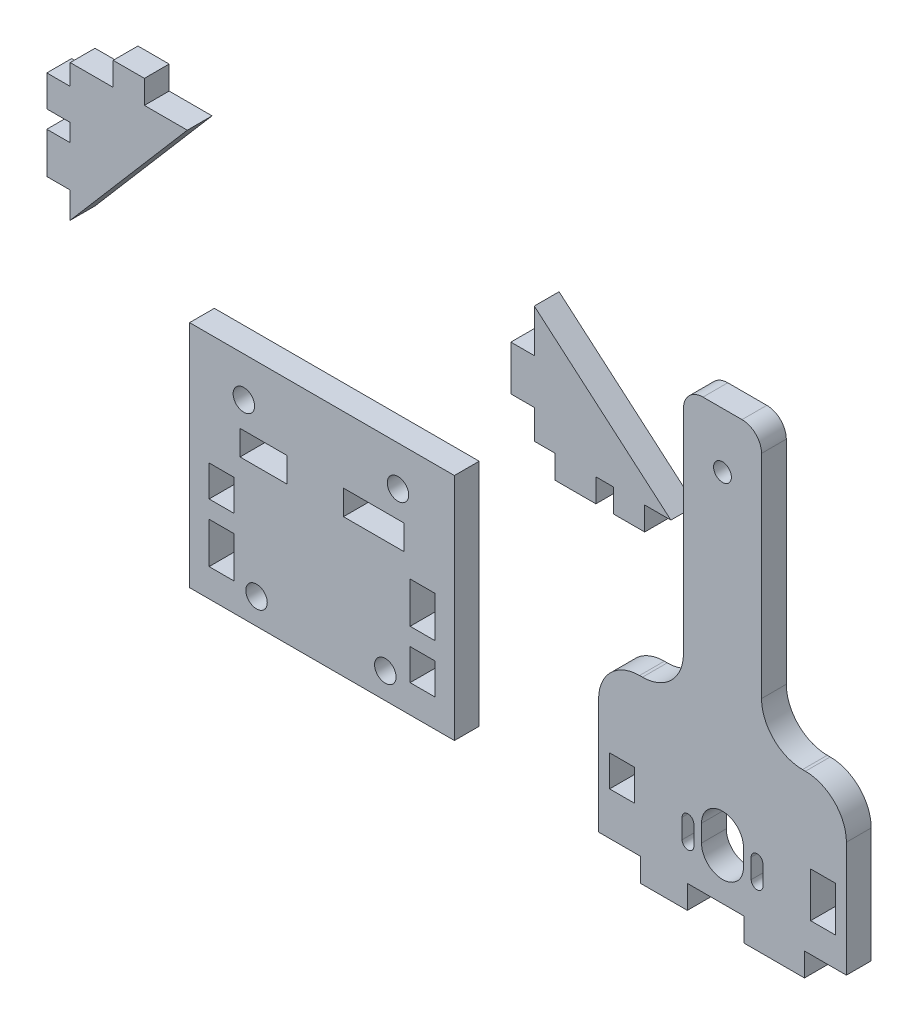
SolidWorks part; units mm, degrees
ref_plane "Front Plane" through (0, 0, 0) normal (0, 0, 1) x (1, 0, 0)
ref_plane "Top Plane" through (0, 0, 0) normal (0, 1, 0) x (1, 0, 0)
ref_plane "Right Plane" through (0, 0, 0) normal (1, 0, 0) x (0, 0, -1)
sketch "Model" plane through (0, 0, 0) normal (0, 0, 1) x (1, 0, 0)
  line L0 (46.0634, 150.8229) -> (46.0634, 142.8229)
  line L1 (46.0634, 138.3229) -> (46.0634, 127.8229)
  line L2 (52.0634, 156.1129) -> (52.0634, 150.8229)
  line L3 (52.0634, 142.8229) -> (52.0634, 138.3229)
  line L4 (52.0634, 127.8229) -> (52.0634, 121.1129)
  line L5 (63.0634, 162.1129) -> (63.0634, 156.1129)
  line L6 (52.0634, 121.1129) -> (82.0634, 156.1129)
  line L7 (71.0634, 156.1129) -> (71.0634, 162.1129)
  line L8 (71.6003, 124.5085) -> (71.6003, 132.5085)
  line L9 (86.6003, 129.5085) -> (86.6003, 124.5085)
  line L10 (87.649, 85.0685) -> (87.649, 77.0685)
  line L11 (87.649, 72.5685) -> (87.649, 62.0685)
  line L12 (93.999, 62.0685) -> (93.999, 72.5685)
  line L13 (93.999, 77.0685) -> (93.999, 85.0685)
  line L14 (95.574, 96.7035) -> (95.574, 90.3535)
  line L15 (198.1866, 47.05) -> (210.1866, 47.05)
  line L16 (224.6866, 47.05) -> (240.1866, 47.05)
  line L17 (187.4366, 53.05) -> (198.1866, 53.05)
  line L18 (210.1866, 53.05) -> (224.6866, 53.05)
  line L19 (240.1866, 53.05) -> (250.9366, 53.05)
  line L20 (107.574, 90.3535) -> (107.574, 96.7035)
  line L21 (63.2366, 54.8885) -> (169.9114, 54.8885)
  line L22 (248.1116, 60.55) -> (241.7616, 60.55)
  line L23 (87.649, 62.0685) -> (93.999, 62.0685)
  line L24 (139.149, 62.0685) -> (145.499, 62.0685)
  line L25 (190.2616, 64.05) -> (196.6116, 64.05)
  line L26 (145.499, 70.0685) -> (139.149, 70.0685)
  line L27 (248.1116, 72.05) -> (241.7616, 72.05)
  line L28 (196.6116, 72.05) -> (190.2616, 72.05)
  line L29 (93.999, 72.5685) -> (87.649, 72.5685)
  line L30 (145.499, 74.5685) -> (139.149, 74.5685)
  line L31 (122.074, 96.7035) -> (122.074, 90.3535)
  line L32 (87.649, 77.0685) -> (93.999, 77.0685)
  line L33 (145.499, 85.0685) -> (139.149, 85.0685)
  line L34 (93.999, 85.0685) -> (87.649, 85.0685)
  line L35 (129.624, 124.2585) -> (129.624, 131.2585)
  line L36 (137.574, 90.3535) -> (137.574, 96.7035)
  line L37 (139.149, 70.0685) -> (139.149, 62.0685)
  line L38 (139.149, 74.5685) -> (139.149, 85.0685)
  line L39 (95.574, 90.3535) -> (107.574, 90.3535)
  line L40 (122.074, 90.3535) -> (137.574, 90.3535)
  line L41 (240.4366, 93.05) -> (239.6866, 93.05)
  line L42 (198.6866, 93.05) -> (197.9366, 93.05)
  line L43 (140.624, 133.2585) -> (140.624, 124.2585)
  line L44 (145.499, 62.0685) -> (145.499, 70.0685)
  line L45 (145.499, 74.5685) -> (145.499, 85.0685)
  line L46 (137.574, 96.7035) -> (122.074, 96.7035)
  line L47 (107.574, 96.7035) -> (95.574, 96.7035)
  line L48 (164.9642, 139.0399) -> (164.9642, 150.5399)
  line L49 (140.624, 124.2585) -> (129.624, 124.2585)
  line L50 (86.6003, 124.5085) -> (71.6003, 124.5085)
  line L51 (176.2542, 125.5399) -> (186.7542, 125.5399)
  line L52 (191.2542, 125.5399) -> (199.2542, 125.5399)
  line L53 (170.9642, 161.5399) -> (170.9642, 150.5399)
  line L54 (170.9642, 139.0399) -> (170.9642, 131.5399)
  line L55 (176.2542, 131.5399) -> (176.2542, 125.5399)
  line L56 (46.0634, 127.8229) -> (52.0634, 127.8229)
  line L57 (170.9642, 131.5399) -> (176.2542, 131.5399)
  line L58 (186.7542, 131.5399) -> (191.2542, 131.5399)
  line L59 (199.2542, 131.5399) -> (205.9642, 131.5399)
  line L60 (71.6003, 132.5085) -> (83.6003, 132.5085)
  line L61 (131.624, 133.2585) -> (140.624, 133.2585)
  line L62 (186.7542, 131.5399) -> (186.7542, 125.5399)
  line L63 (187.4366, 82.55) -> (187.4366, 53.05)
  line L64 (190.2616, 72.05) -> (190.2616, 64.05)
  line L65 (191.2542, 131.5399) -> (191.2542, 125.5399)
  line L66 (52.0634, 138.3229) -> (46.0634, 138.3229)
  line L67 (170.9642, 139.0399) -> (164.9642, 139.0399)
  line L68 (46.0634, 142.8229) -> (52.0634, 142.8229)
  line L69 (196.6116, 64.05) -> (196.6116, 72.05)
  line L70 (198.1866, 53.05) -> (198.1866, 47.05)
  line L71 (199.2542, 125.5399) -> (199.2542, 131.5399)
  line L72 (170.9642, 150.5399) -> (164.9642, 150.5399)
  line L73 (52.0634, 150.8229) -> (46.0634, 150.8229)
  line L74 (82.0634, 156.1129) -> (71.0634, 156.1129)
  line L75 (63.0634, 156.1129) -> (52.0634, 156.1129)
  line L76 (208.8366, 67.05) -> (208.8366, 62.05)
  line L77 (209.1866, 157.95) -> (209.1866, 103.55)
  line L78 (210.1866, 47.05) -> (210.1866, 53.05)
  line L79 (211.8366, 62.05) -> (211.8366, 67.05)
  line L80 (71.0634, 162.1129) -> (63.0634, 162.1129)
  line L81 (224.1866, 162.95) -> (214.1866, 162.95)
  line L82 (205.9642, 131.5399) -> (170.9642, 161.5399)
  line L83 (212.8116, 68.2) -> (212.8116, 63.8)
  line L84 (224.6866, 53.05) -> (224.6866, 47.05)
  line L85 (225.5616, 63.8) -> (225.5616, 68.2)
  line L86 (226.5366, 67.05) -> (226.5366, 62.05)
  line L87 (229.1866, 103.55) -> (229.1866, 157.95)
  line L88 (229.5366, 62.05) -> (229.5366, 67.05)
  line L89 (240.1866, 47.05) -> (240.1866, 53.05)
  line L90 (241.7616, 60.55) -> (241.7616, 72.05)
  line L91 (248.1116, 60.55) -> (248.1116, 72.05)
  line L92 (250.9366, 53.05) -> (250.9366, 82.55)
  arc A0 (169.9114, 54.8885) -> (63.2366, 54.8885) centre (116.574, 92.0385) ccw
  arc A1 (229.1866, 103.55) -> (239.6866, 93.05) centre (239.6866, 103.55) ccw
  arc A2 (250.9366, 82.55) -> (240.4366, 93.05) centre (240.4366, 82.55) ccw
  arc A3 (197.9366, 93.05) -> (187.4366, 82.55) centre (197.9366, 82.55) ccw
  arc A4 (198.6866, 93.05) -> (209.1866, 103.55) centre (198.6866, 103.55) ccw
  arc A5 (225.5616, 68.2) -> (212.8116, 68.2) centre (219.1866, 68.2) ccw
  arc A6 (212.8116, 63.8) -> (225.5616, 63.8) centre (219.1866, 63.8) ccw
  arc A7 (214.1866, 162.95) -> (209.1866, 157.95) centre (214.1866, 157.95) ccw
  arc A8 (229.1866, 157.95) -> (224.1866, 162.95) centre (224.1866, 157.95) ccw
  arc A9 (86.6003, 129.5085) -> (83.6003, 132.5085) centre (83.6003, 129.5085) ccw
  circle A10 centre (219.1866, 148.81) radius 2.285
  circle A11 centre (78.574, 66.1385) radius 2.2
  circle A12 centre (154.574, 66.1385) radius 2.2
  circle A13 centre (83.574, 117.8885) radius 2.2
  circle A14 centre (149.574, 117.8885) radius 2.2
  arc A15 (131.624, 133.2585) -> (129.624, 131.2585) centre (131.624, 131.2585) ccw
  arc A16 (226.5366, 62.05) -> (229.5366, 62.05) centre (228.0366, 62.05) ccw
  arc A17 (229.5366, 67.05) -> (226.5366, 67.05) centre (228.0366, 67.05) ccw
  arc A18 (208.8366, 62.05) -> (211.8366, 62.05) centre (210.3366, 62.05) ccw
  arc A19 (211.8366, 67.05) -> (208.8366, 67.05) centre (210.3366, 67.05) ccw
extrude "Boss-Extrude1" add sketch "Model" along normal blind 6.35
sketch "Sketch2" plane through (0, 0, 6.35) normal (0, 0, 1) x (1, 0, 0)
  line L0 (219.1866, 68.2) -> (219.1866, 63.8) construction
  line L1 (224.5616, 68.2) -> (224.5616, 63.8)
  line L2 (213.8116, 68.2) -> (213.8116, 63.8)
  line L3 (225.5616, 63.8) -> (225.5616, 68.2) construction
  line L4 (219.1866, 68.2) -> (219.1866, 63.8) construction
  line L5 (226.1415, 68.2) -> (226.1415, 63.8)
  line L6 (212.2318, 68.2) -> (212.2318, 63.8)
  arc A0 (224.5616, 68.2) -> (213.8116, 68.2) centre (219.1866, 68.2) ccw
  arc A1 (213.8116, 63.8) -> (224.5616, 63.8) centre (219.1866, 63.8) ccw
  arc A2 (226.1415, 68.2) -> (212.2318, 68.2) centre (219.1866, 68.2) ccw
  arc A3 (212.2318, 63.8) -> (226.1415, 63.8) centre (219.1866, 63.8) ccw
  point P4 (219.1866, 66)
  point P13 (219.1866, 66)
  dimension "D1" = 1
extrude "Boss-Extrude2" add sketch "Sketch2" against normal up to surface (6.35 mm away) up to face at (244.9366, 66.3, 0)
sketch "Sketch4" plane through (0, 0, 6.35) normal (0, 0, 1) x (1, 0, 0)
  line L0 (63.2366, 54.8885) -> (169.9114, 54.8885) construction
  line L2 (82.649, 54.8885) -> (82.649, 113.7035)
  line L3 (82.649, 113.7035) -> (150.499, 113.7035)
  line L4 (150.499, 54.8885) -> (150.499, 113.7035)
  line L5 (87.649, 72.5685) -> (87.649, 62.0685) construction
  line L6 (145.499, 62.0685) -> (145.499, 70.0685) construction
  line L7 (137.574, 96.7035) -> (122.074, 96.7035) construction
  line L8 (82.649, 54.8885) -> (31.6701, 45.7244)
  line L9 (31.6701, 45.7244) -> (55.3205, 121.4654)
  line L10 (55.3205, 121.4654) -> (94.6879, 166.8203)
  line L11 (94.6879, 166.8203) -> (153.5145, 163.0781)
  line L12 (153.5145, 163.0781) -> (161.8969, 140.7749)
  line L13 (161.8969, 140.7749) -> (181.2064, 118.0227)
  line L14 (181.2064, 118.0227) -> (187.5485, 101.148)
  line L15 (187.5485, 101.148) -> (177.4642, 45.7244)
  line L16 (177.4642, 45.7244) -> (150.499, 54.8885)
  dimension "D1" = 5
  dimension "D2" = 5
  dimension "D3" = 17
extrude "Cut-Extrude2" cut sketch "Sketch4" against normal blind 10
sketch "Sketch5" plane through (0, 0, 6.35) normal (0, 0, 1) x (1, 0, 0)
  line L0 (82.649, 61.5062) -> (150.499, 61.5062) construction
  line L1 (82.649, 54.8885) -> (82.649, 113.7035) construction
  line L2 (150.499, 113.7035) -> (150.499, 54.8885) construction
  line L3 (82.649, 103.5062) -> (150.499, 103.5062) construction
  line L4 (136.0486, 103.5062) -> (136.0486, 61.5062) construction
  circle A0 centre (99.7986, 61.5062) radius 2.75
  circle A1 centre (132.7986, 61.5062) radius 2.75
  circle A2 centre (96.5486, 103.5062) radius 2.75
  circle A3 centre (136.0486, 103.5062) radius 2.75
  dimension "D1" = 5.5
  dimension "D2" = 5.5
  dimension "D4" = 5.5
  dimension "D5" = 5.5
  dimension "D3" = 33
  dimension "D6" = 39.5
  dimension "D7" = 42
  dimension "D8" = 3.25
extrude "Cut-Extrude3" cut sketch "Sketch5" against normal blind 10
sketch "Sketch6" plane through (0, 0, 6.35) normal (0, 0, 1) x (1, 0, 0)
  line L1 (42.8966, 167.7184) -> (253.804, 167.7184)
  line L2 (42.8966, 167.7184) -> (42.8966, 43.3294)
  line L3 (42.8966, 43.3294) -> (253.804, 43.3294)
  line L4 (253.804, 167.7184) -> (253.804, 43.3294)
